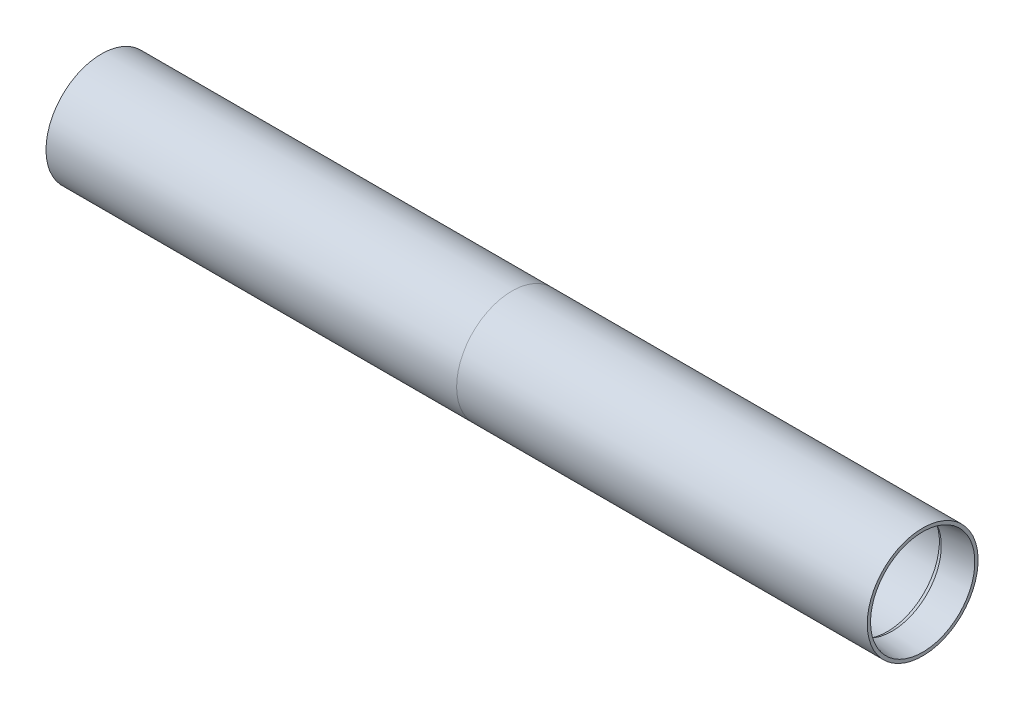
SolidWorks part; units mm, degrees
other "End Section"
other "Middle Section"
other "Coupler"
ref_plane "Front Plane" through (0, 0, 0) normal (0, 0, 1) x (1, 0, 0)
ref_plane "Top Plane" through (0, 0, 0) normal (0, 1, 0) x (1, 0, 0)
ref_plane "Right Plane" through (0, 0, 0) normal (1, 0, 0) x (0, 0, -1)
sketch "Sketch1" plane through (0, 0, 0) normal (0, 1, 0) x (1, 0, 0)
  line L0 (0, 0) -> (200, 0) construction
  line L1 (200, 0) -> (200, 25.4) construction
  line L2 (0, 0) -> (0, 25.4) construction
  line L3 (200, 25.4) -> (185, 24.0877)
  line L4 (0, 25.4) -> (182.727, 25.4)
  line L5 (0, 25.4) -> (0, 27)
  line L6 (0, 27) -> (200, 27)
  line L7 (200, 25.4) -> (200, 27)
  line L8 (185, 24.0877) -> (182.727, 25.4)
  line L9 (185, 24.0877) -> (185, 25.4) construction
  line L10 (182.727, 25.4) -> (200, 25.4) construction
  dimension "D1" = 1.6
  dimension "D2" = 200
  dimension "D3" = 27
  dimension "D4" = 5
  dimension "D5" = 15
  dimension "D6" = 30
revolve "Revolve1" add sketch "Sketch1" angle 360 about L0
sketch "Sketch2" plane through (0, 0, 0) normal (0, 1, 0) x (1, 0, 0)
  line L0 (0, 25.4) -> (0, 27) construction
  line L1 (0, 27) -> (200, 27) construction
  line L2 (200, 25.4) -> (200, 27) construction
  line L3 (0, 25.4) -> (182.727, 25.4) construction
  line L4 (185, 24.0877) -> (182.727, 25.4) construction
  line L5 (200, 25.4) -> (185, 24.0877) construction
  line L6 (0, 25.4) -> (0, 27) construction
  line L7 (0, 27) -> (400, 27) construction
  line L8 (200, 25.4) -> (200, 27) construction
  line L9 (0, 25.4) -> (182.727, 25.4) construction
  line L10 (185, 24.0877) -> (182.727, 25.4) construction
  line L11 (200, 25.4) -> (185, 24.0877) construction
  line L12 (200, -27) -> (200, 27) construction
  line L13 (400, 25.4) -> (400, 27) construction
  line L14 (382.727, 25.4) -> (217.273, 25.4)
  line L15 (215, 24.0877) -> (217.273, 25.4)
  line L16 (200, 25.4) -> (215, 24.0877)
  line L17 (200, -27) -> (400, -27) construction
  line L18 (300, -27) -> (300, 24.0877) construction
  line L19 (400, 25.4) -> (400, -27) construction
  line L20 (385, 24.0877) -> (382.727, 25.4)
  line L21 (400, 25.4) -> (385, 24.0877)
  line L22 (400, 27) -> (400, 25.4)
  line L23 (200, 27) -> (200, 25.4)
  line L24 (200, 27) -> (400, 27)
revolve "Revolve2" add sketch "Sketch2" angle 360 about L0
sketch "Sketch4" plane through (0, 0, 0) normal (0, 1, 0) x (1, 0, 0)
  line L0 (200, 25.4) -> (185, 24.0877) construction
  line L1 (200, 25.4) -> (185, 24.0877) construction
  line L2 (200, 0) -> (200, 25.4) construction
  line L3 (200, 0) -> (200, 25.4) construction
  line L4 (200, 25.4) -> (215, 24.0877) construction
  line L5 (200, 25.2996) -> (185.0087, 23.9881)
  line L6 (200, 25.2996) -> (214.9913, 23.9881)
  line L7 (214.9913, 23.9881) -> (214.9913, 22.9881)
  line L8 (214.9913, 22.9881) -> (185.0087, 22.9881)
  line L9 (185.0087, 22.9881) -> (185.0087, 23.9881)
  line L10 (0, 0) -> (200, 0) construction
  line L11 (0, 0) -> (200, 0) construction
  dimension "D2" = 1
  dimension "D1" = 0.1
revolve "Revolve3" add sketch "Sketch4" angle 360 about L0
